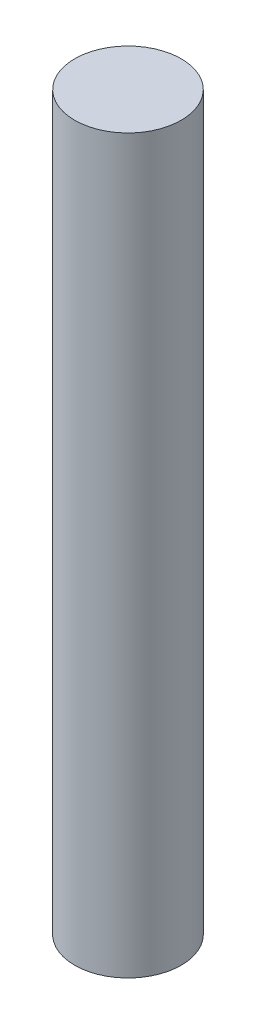
SolidWorks part; units mm, degrees
ref_plane "Alzado" through (0, 0, 0) normal (0, 0, 1) x (1, 0, 0)
ref_plane "Planta" through (0, 0, 0) normal (0, 1, 0) x (1, 0, 0)
ref_plane "Vista lateral" through (0, 0, 0) normal (1, 0, 0) x (0, 0, -1)
sketch "Croquis1" plane through (0, 0, 0) normal (0, 1, 0) x (1, 0, 0)
  circle A0 centre (0, 0) radius 2.475
  dimension "D1" = 4.95
extrude "Saliente-Extruir1" add sketch "Croquis1" along normal blind 34
